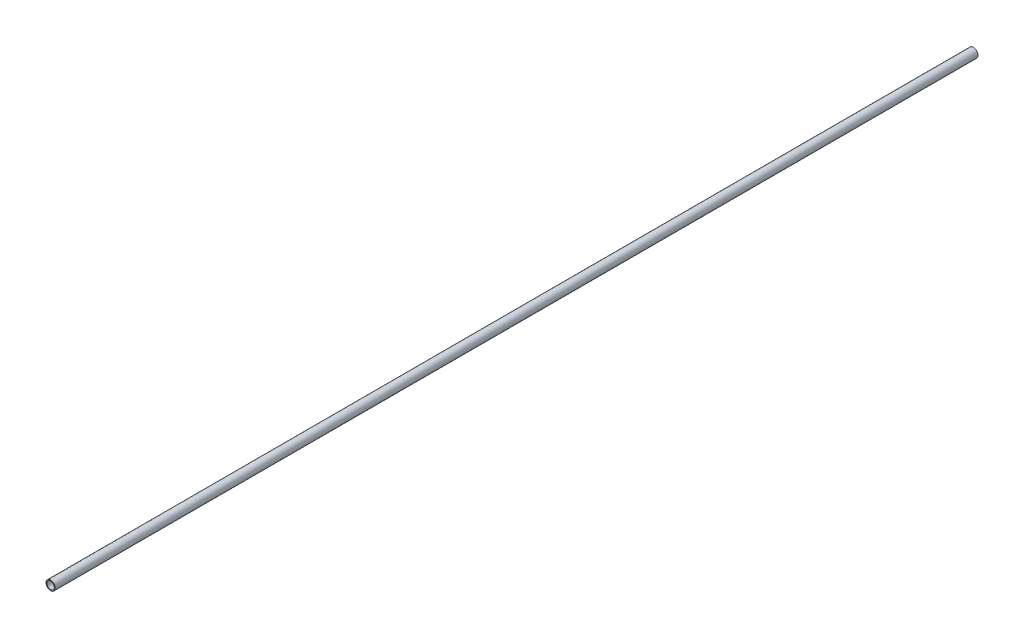
SolidWorks part; units mm, degrees
material "Poltrusion Carbon Fiber"
ref_plane "Front Plane" through (0, 0, 0) normal (0, 0, 1) x (1, 0, 0)
ref_plane "Top Plane" through (0, 0, 0) normal (0, 1, 0) x (1, 0, 0)
ref_plane "Right Plane" through (0, 0, 0) normal (1, 0, 0) x (0, 0, -1)
sketch "Эскиз1" plane through (0, 0, 0) normal (0, 0, 1) x (1, 0, 0)
  circle A0 centre (0, 0) radius 5
  circle A1 centre (0, 0) radius 4
  dimension "D1" = 10
  dimension "D2" = 1
extrude "Бобышка-Вытянуть1" add sketch "Эскиз1" along normal mid plane 1000
